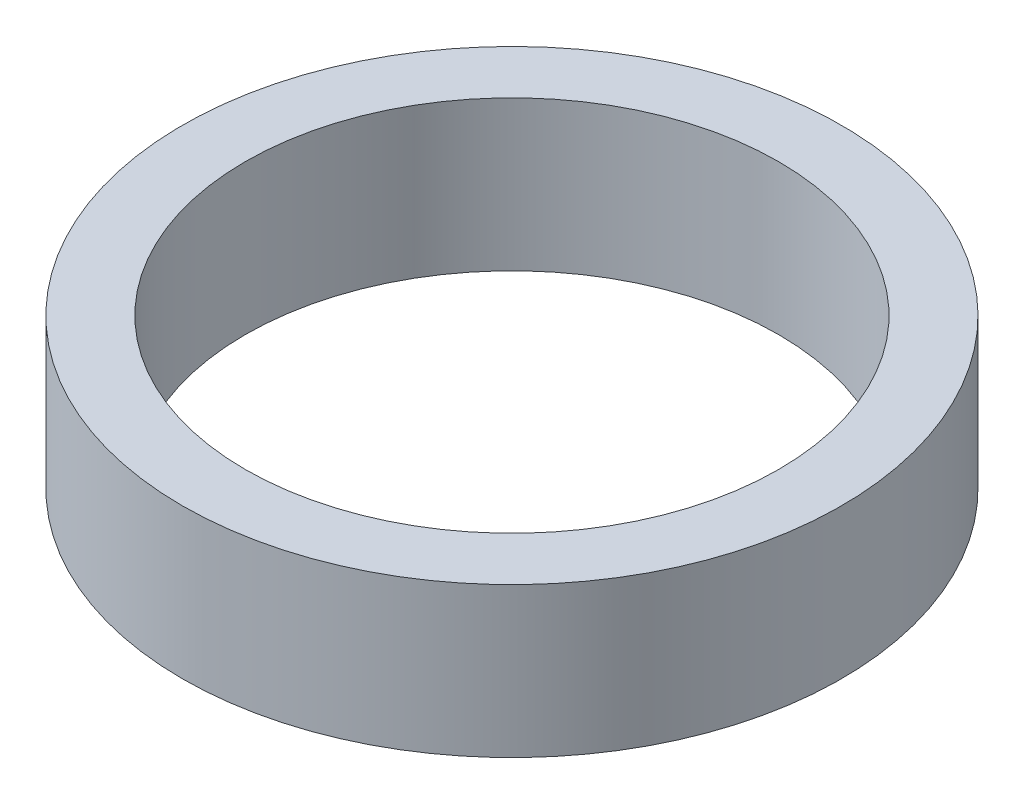
SolidWorks part; units mm, degrees
material "PTFE (general)"
ref_plane "Front Plane" through (0, 0, 0) normal (0, 0, 1) x (1, 0, 0)
ref_plane "Top Plane" through (0, 0, 0) normal (0, 1, 0) x (1, 0, 0)
ref_plane "Right Plane" through (0, 0, 0) normal (1, 0, 0) x (0, 0, -1)
sketch "Sketch1" plane through (0, 0, 0) normal (0, 1, 0) x (1, 0, 0)
  circle A0 centre (0, 0) radius 11
  circle A1 centre (0, 0) radius 8.9
  dimension "D1" = 17.8
  dimension "D2" = 22
extrude "Boss-Extrude1" add sketch "Sketch1" along normal blind 5
